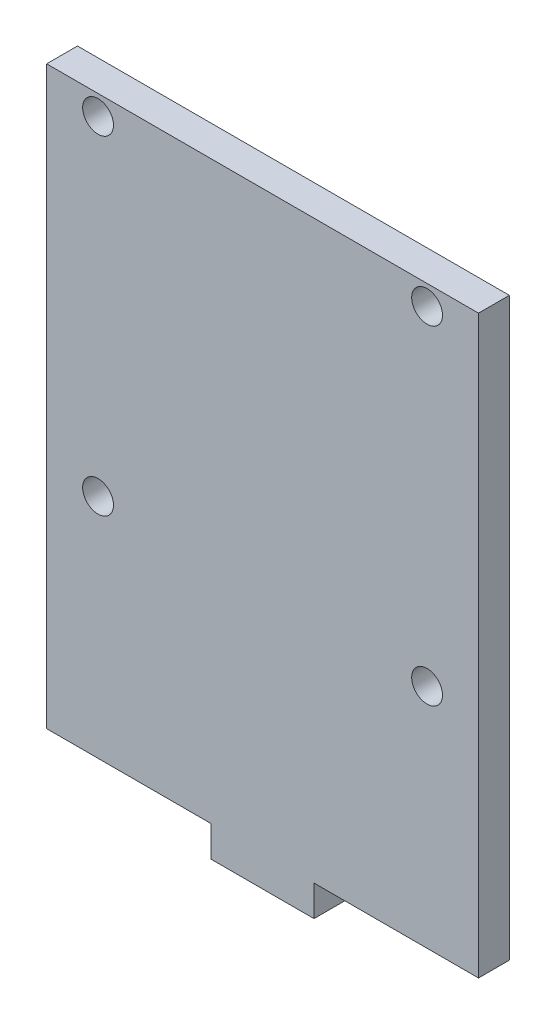
SolidWorks part; units mm, degrees
ref_plane "Front Plane" through (0, 0, 0) normal (0, 0, 1) x (1, 0, 0)
ref_plane "Top Plane" through (0, 0, 0) normal (0, 1, 0) x (1, 0, 0)
ref_plane "Right Plane" through (0, 0, 0) normal (1, 0, 0) x (0, 0, -1)
sketch "Sketch1" plane through (0, 0, 0) normal (0, 0, 1) x (1, 0, 0)
  line L1 (5, -29.5) -> (-5, -29.5)
  line L2 (21, -26.5) -> (21, 29.5)
  line L3 (21, 29.5) -> (-21, 29.5)
  line L4 (-21, -26.5) -> (-21, 29.5)
  line L5 (18.8644, -26.5) -> (-21, 29.5) construction
  line L6 (21, 29.5) -> (-18.8644, -26.5) construction
  line L7 (-5, -29.5) -> (-5, -26.5)
  line L13 (5, -26.5) -> (5, -29.5)
  line L14 (-21, -26.5) -> (-5, -26.5)
  line L15 (5, -26.5) -> (21, -26.5)
  circle A0 centre (-16, 27.5692) radius 1.5
  circle A1 centre (-16, -4.4308) radius 1.5
  circle A2 centre (16, -4.4308) radius 1.5
  circle A3 centre (16, 27.5692) radius 1.5
  point P0 (0, 0)
  point P8 (0, 11.5692)
  dimension "D5" = 3
  dimension "D6" = 3
  dimension "D7" = 3
  dimension "D8" = 3
  dimension "D3" = 32
  dimension "D4" = 32
  dimension "D9" = 10
  dimension "D10" = 3
  dimension "D11" = 16
extrude "Boss-Extrude1" add sketch "Sketch1" along normal blind 3
